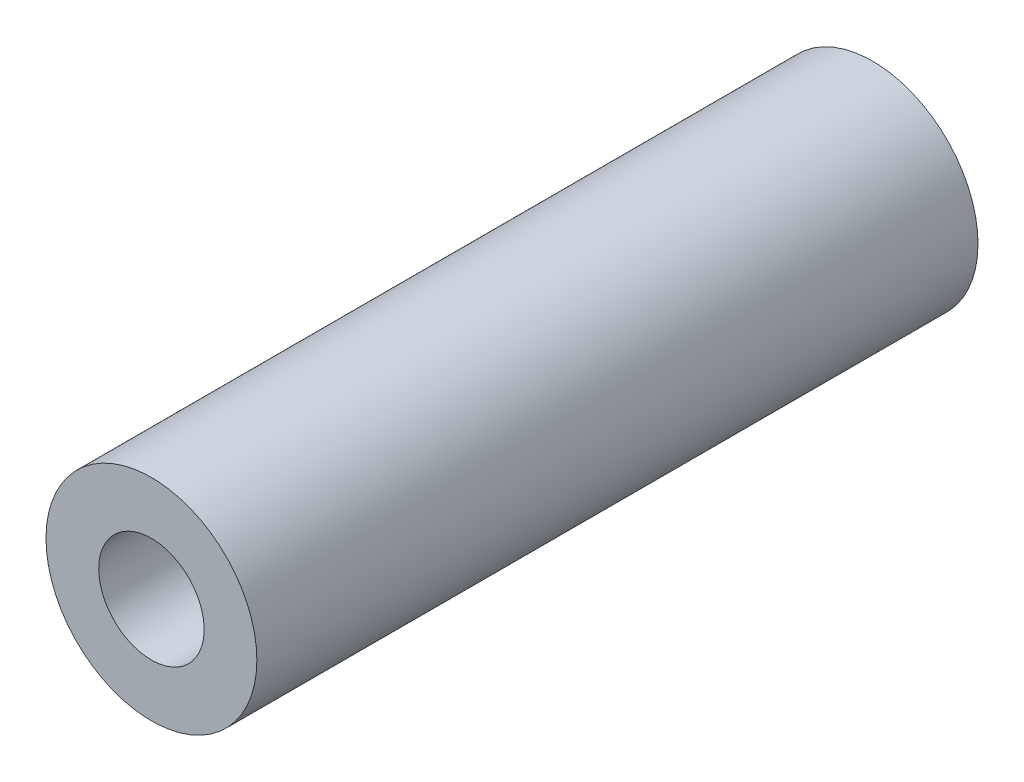
SolidWorks part; units mm, degrees
material "1060 Alloy"
ref_plane "Front Plane" through (0, 0, 0) normal (0, 0, 1) x (1, 0, 0)
ref_plane "Top Plane" through (0, 0, 0) normal (0, 1, 0) x (1, 0, 0)
ref_plane "Right Plane" through (0, 0, 0) normal (1, 0, 0) x (0, 0, -1)
sketch "Sketch2" plane through (0, 0, 0) normal (0, 0, 1) x (1, 0, 0)
  circle A0 centre (0, 0) radius 6.35
  circle A1 centre (0, 0) radius 3.175
  dimension "D1" = 12.7
  dimension "D2" = 6.35
extrude "Boss-Extrude1" add sketch "Sketch2" along normal blind 43.434
